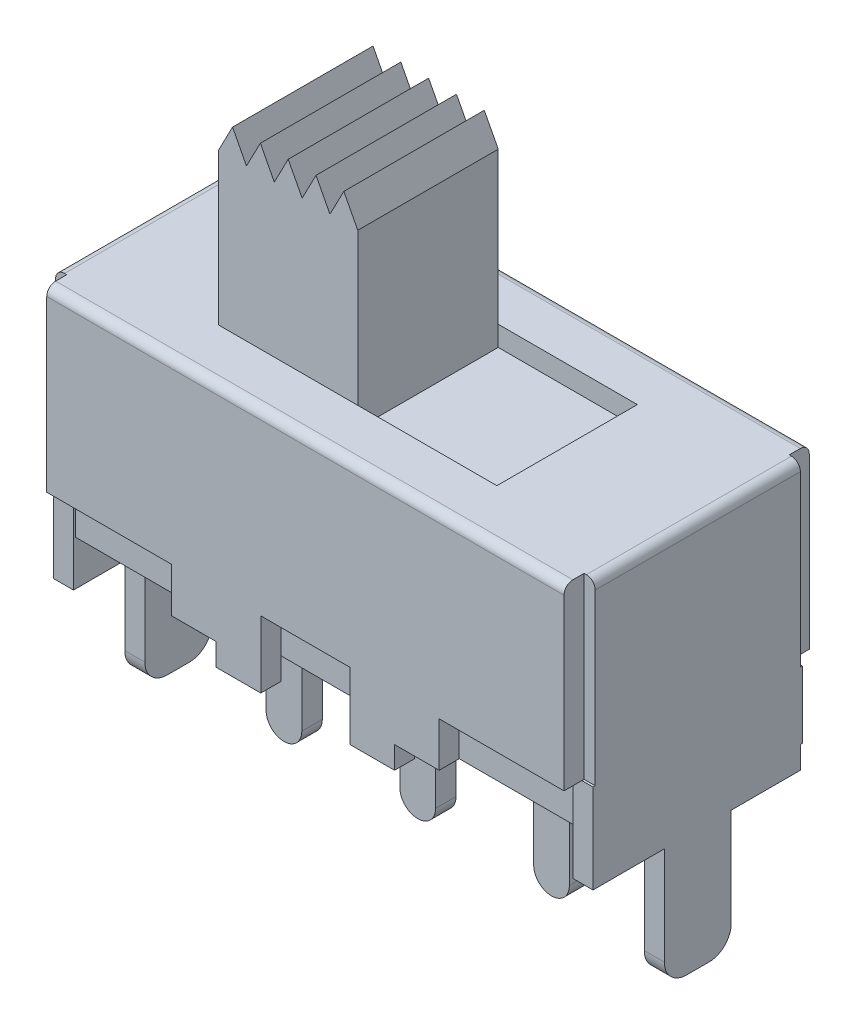
SolidWorks part; units mm, degrees
ref_plane "前视基准面" through (0, 0, 0) normal (0, 0, 1) x (1, 0, 0)
ref_plane "上视基准面" through (0, 0, 0) normal (0, 1, 0) x (1, 0, 0)
ref_plane "右视基准面" through (0, 0, 0) normal (1, 0, 0) x (0, 0, -1)
sketch "草图1" plane through (0, 0, 0) normal (0, 1, 0) x (1, 0, 0)
  line L0 (0, 0) -> (11.2, 0)
  line L1 (11.2, 0) -> (11.2, 4.6)
  line L2 (11.2, 4.6) -> (0, 4.6)
  line L3 (0, 4.6) -> (0, 0)
extrude "凸台-拉伸1" add sketch "草图1" along normal blind 5
sketch "草图2" plane through (0, 0, 0) normal (0, 0, 1) x (1, 0, 0)
  line L1 (11.4, 5) -> (11.4, 1)
  line L2 (11.4, 1) -> (8.6, 1)
  line L3 (-0.2, 1) -> (-0.2, 5)
  line L5 (11.4, 5) -> (-0.2, 5)
  line L7 (5.6, 1) -> (6.6, 1)
  line L8 (6.6, 1) -> (6.6, -0.5)
  line L9 (6.6, -0.5) -> (7.6, -0.5)
  line L10 (7.6, -0.5) -> (7.6, 0)
  line L11 (11.2, 0) -> (0, 0) construction
  line L12 (7.6, 0) -> (8.6, 0)
  line L13 (8.6, 0) -> (8.6, 1)
  line L14 (5.6, 1) -> (4.6, 1)
  line L15 (4.6, 1) -> (4.6, -0.5)
  line L16 (4.6, -0.5) -> (3.6, -0.5)
  line L17 (3.6, -0.5) -> (3.6, 0)
  line L18 (3.6, 0) -> (2.6, 0)
  line L19 (2.6, 0) -> (2.6, 1)
  line L20 (2.6, 1) -> (-0.2, 1)
extrude "凸台-拉伸2" add sketch "草图2" along normal blind 0.45
sketch "草图3" plane through (0, 0, -4.6) normal (0, 0, -1) x (-1, 0, 0)
  line L0 (-5.6, 5) -> (-11.4, 5)
  line L1 (-11.2, 5) -> (0, 5) construction
  line L2 (-11.4, 5) -> (-11.4, 1)
  line L3 (-11.4, 1) -> (-8.6, 1)
  line L4 (0.2, 1) -> (0.2, 5)
  line L5 (0.2, 5) -> (-5.6, 5)
  line L6 (-6.6, -0.5) -> (-6.6, 1)
  line L7 (-6.6, 1) -> (-4.6, 1)
  line L8 (-4.6, -0.5) -> (-4.6, 1)
  line L10 (-3.6, -0.5) -> (-4.6, -0.5)
  line L11 (-6.6, -0.5) -> (-7.6, -0.5)
  line L12 (-6.6, -0.5) -> (-7.6, -0.5) construction
  line L13 (-7.6, -0.5) -> (-7.6, 0)
  line L14 (-11.2, 0) -> (0, 0) construction
  line L15 (-7.6, -0.5) -> (-7.6, 0) construction
  line L16 (-7.6, 0) -> (-8.6, 0)
  line L17 (-8.6, 0) -> (-8.6, 1)
  line L18 (-3.6, -0.5) -> (-3.6, 0)
  line L19 (-3.6, 0) -> (-2.6, 0)
  line L20 (-2.6, 0) -> (-2.6, 1)
  line L21 (-2.6, 1) -> (0.2, 1)
extrude "凸台-拉伸3" add sketch "草图3" along normal blind 0.45
sketch "草图4" plane through (11.2, 0, 0) normal (1, 0, 0) x (0, 0, -1)
  line L0 (0, 5) -> (0, 1)
  line L1 (0, -1) -> (1.55, -1)
  line L2 (4.6, -1) -> (4.6, -0.5)
  line L3 (4.6, 5) -> (0, 5)
  line L4 (0, 1) -> (-0.05, 1)
  line L5 (2.3, -3.7) -> (2.05, -3.7)
  line L6 (1.55, -3.2) -> (1.55, -1)
  line L8 (3.05, -1) -> (3.05, -3.2)
  line L9 (2.55, -3.7) -> (2.3, -3.7)
  line L10 (3.05, -1) -> (4.6, -1)
  line L12 (-0.45, 1) -> (0, 1) construction
  line L13 (-0.05, 1) -> (-0.05, -1)
  line L14 (-0.05, -1) -> (0, -1)
  line L15 (4.6, 1) -> (4.65, 1)
  line L16 (5.05, 1) -> (4.6, 1) construction
  line L17 (4.65, 1) -> (4.65, -0.5)
  line L18 (5.05, -0.5) -> (4.6, -0.5) construction
  line L19 (4.65, -0.5) -> (4.6, -0.5)
  line L20 (4.6, 1) -> (4.6, 5)
  arc A0 (3.05, -3.2) -> (2.55, -3.7) centre (2.55, -3.2) cw
  arc A1 (2.05, -3.7) -> (1.55, -3.2) centre (2.05, -3.2) cw
  dimension "D1" = 0.5
extrude "凸台-拉伸4" add sketch "草图4" along normal blind 0.45
sketch "草图5" plane through (0, 0, 0) normal (-1, 0, 0) x (0, 0, 1)
  line L0 (-4.6, 5) -> (-4.6, 1)
  line L1 (-4.6, -1) -> (-3.05, -1)
  line L2 (-3.05, -1) -> (-3.05, -3.2)
  line L3 (-2.55, -3.7) -> (-2.05, -3.7)
  line L4 (-1.55, -3.2) -> (-1.55, -1)
  line L5 (-1.55, -1) -> (0.05, -1)
  line L6 (0.05, 1) -> (0.05, -1) construction
  line L7 (0.05, -1) -> (-1.55, -1) construction
  line L8 (0.05, -1) -> (0.05, 1)
  line L9 (0.45, 1) -> (0, 1) construction
  line L10 (0.45, 1) -> (0, 1) construction
  line L11 (0.05, 1) -> (0, 1)
  line L12 (0, 1) -> (0, 5)
  line L13 (0, 5) -> (-4.6, 5)
  line L14 (-4.6, 1) -> (-4.65, 1)
  line L15 (-5.05, 1) -> (-4.6, 1) construction
  line L16 (-4.65, 1) -> (-4.65, -1)
  line L17 (-4.65, -1) -> (-4.6, -1)
  arc A0 (-2.05, -3.7) -> (-1.55, -3.2) centre (-2.05, -3.2) ccw
  arc A1 (-2.55, -3.7) -> (-3.05, -3.2) centre (-2.55, -3.2) cw
  dimension "D1" = 0.5
extrude "凸台-拉伸5" add sketch "草图5" along normal blind 0.45
sketch "草图6" plane through (0, 5, 0) normal (0, 1, 0) x (1, 0, 0)
  line L3 (2.48, 2.3) -> (2.48, 3.875)
  line L4 (2.48, 3.875) -> (8.72, 3.875)
  line L5 (8.72, 3.875) -> (8.72, 0.725)
  line L6 (8.72, 0.725) -> (2.48, 0.725)
  line L7 (2.48, 0.725) -> (2.48, 2.3)
extrude "切除-拉伸1" cut sketch "草图6" against normal blind 0.45
sketch "草图7" plane through (0, 4.55, 0) normal (0, 1, 0) x (1, 0, 0)
  line L0 (2.48, 3.875) -> (5.6, 3.875)
  line L4 (8.72, 3.875) -> (2.48, 3.875) construction
  line L5 (5.6, 3.875) -> (5.6, 0.725)
  line L6 (2.48, 0.725) -> (8.72, 0.725) construction
  line L7 (5.6, 0.725) -> (2.48, 0.725)
  line L8 (2.48, 0.725) -> (2.48, 3.875)
extrude "凸台-拉伸6" add sketch "草图7" along normal blind 4.45
sketch "草图8" plane through (0, 0, -0.725) normal (0, 0, 1) x (1, 0, 0)
  line L0 (4.664, 9) -> (4.976, 8.4)
  line L2 (5.6, 9) -> (5.6, 5) construction
  line L4 (4.976, 8.4) -> (5.288, 9)
  line L5 (2.48, 9) -> (5.6, 9) construction
  line L6 (5.288, 9) -> (5.6, 8.4)
  line L7 (4.352, 8.4) -> (4.664, 9)
  line L8 (4.04, 9) -> (4.352, 8.4)
  line L9 (3.728, 8.4) -> (4.04, 9)
  line L10 (3.416, 9) -> (3.728, 8.4)
  line L11 (3.104, 8.4) -> (3.416, 9)
  line L12 (2.792, 9) -> (3.104, 8.4)
  line L13 (2.48, 8.4) -> (2.792, 9)
  line L14 (2.48, 8.4) -> (2.48, 9)
  line L15 (2.48, 9) -> (5.6, 9)
  line L16 (5.6, 9) -> (5.6, 8.4)
  line M6 (5.6, 5) -> (5.6, 9)
  line M7 (5.6, 9) -> (2.48, 9)
  line M8 (2.48, 9) -> (2.48, 5)
extrude "切除-拉伸2" cut sketch "草图8" against normal blind 4.45 contours L13 M8 M7 | L12 L11 M7 | L10 L9 M7 | L8 L7 M7 | L0 L4 M7 | L6 M7 M6
sketch "草图9" plane through (0, 0, 0) normal (0, -1, 0) x (1, 0, 0)
  line L0 (8.2, -2.3) -> (8.2, -2.07)
  line L2 (8.2, -2.53) -> (8.2, -2.3)
  line L3 (5.2, -2.3) -> (5.2, -2.07)
  line L4 (5.2, -2.07) -> (6, -2.07)
  line L5 (6, -2.07) -> (6, -2.3)
  line L6 (6, -2.3) -> (6, -2.53)
  line L7 (6, -2.53) -> (5.2, -2.53)
  line L8 (5.2, -2.53) -> (5.2, -2.3)
  line L9 (9, -2.3) -> (9, -2.53)
  line L10 (9, -2.53) -> (8.2, -2.53)
  line L11 (8.2, -2.07) -> (9, -2.07)
  line L12 (9, -2.07) -> (9, -2.3)
  line L13 (2.2, -2.3) -> (2.2, -2.07)
  line L14 (2.2, -2.53) -> (2.2, -2.3)
  line L15 (3, -2.3) -> (3, -2.53)
  line L16 (3, -2.53) -> (2.2, -2.53)
  line L17 (2.2, -2.07) -> (3, -2.07)
  line L18 (3, -2.07) -> (3, -2.3)
extrude "凸台-拉伸7" add sketch "草图9" along normal blind 3.7
sketch "草图10" plane through (0, 0, -2.07) normal (0, 0, 1) x (1, 0, 0)
  line L0 (2.2, -3.3) -> (2.2, -3.7)
  line L2 (2.2, -3.7) -> (9, -3.7)
  line L3 (9, -3.7) -> (9, -3.3)
  line L5 (3, -3.7) -> (3, 0) construction
  line L6 (2.2, -3.7) -> (2.2, 0) construction
  line L7 (6, -3.7) -> (6, 0) construction
  line L8 (8.2, -3.7) -> (8.2, 0) construction
  line L9 (9, -3.7) -> (9, 0) construction
  line L10 (8.2, -3.3) -> (6, -3.3)
  line L11 (5.2, -3.3) -> (3, -3.3)
  arc A0 (3, -3.3) -> (2.2, -3.3) centre (2.6, -3.3) cw
  arc A1 (6, -3.3) -> (5.2, -3.3) centre (5.6, -3.3) cw
  arc A2 (8.2, -3.3) -> (9, -3.3) centre (8.6, -3.3) ccw
  line M2 (2.2, 0) -> (2.2, -3.7)
  line M3 (2.2, -3.7) -> (3, -3.7)
  line M4 (3, -3.7) -> (3, 0)
extrude "切除-拉伸3" cut sketch "草图10" against normal blind 3.7 contours A0 M3 M2 | A0 L2 M4 | L2 A1 L11 M4 | A2 L10 A1 L2 | A2 L2 L3
fillet "圆角1" radius 0.2 1 edges at (-0.45, 5, -2.3)
fillet "圆角2" radius 0.2 1 edges at (5.6, 5, 0.45)
fillet "圆角3" radius 0.2 1 edges at (11.65, 5, -2.3)
fillet "圆角4" radius 0.2 1 edges at (5.6, 5, -5.05)
